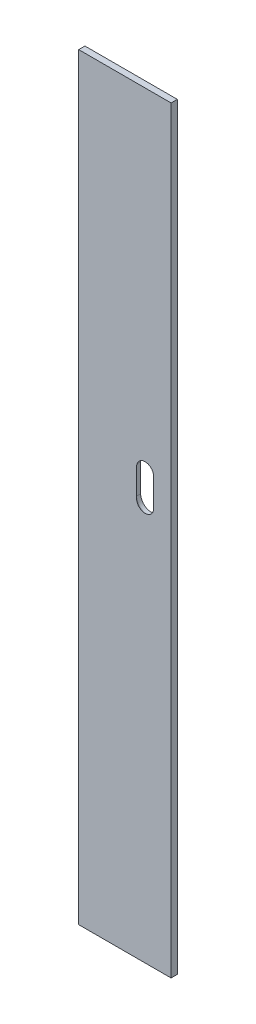
SolidWorks part; units mm, degrees
ref_plane "Front Plane" through (0, 0, 0) normal (0, 0, 1) x (1, 0, 0)
ref_plane "Top Plane" through (0, 0, 0) normal (0, 1, 0) x (1, 0, 0)
ref_plane "Right Plane" through (0, 0, 0) normal (1, 0, 0) x (0, 0, -1)
sketch "Sketch1" plane through (0, 0, 0) normal (0, 0, 1) x (1, 0, 0)
  line L1 (37, -17.9) -> (-230, -17.9)
  line L2 (37, -17.9) -> (37, 2172.1)
  line L3 (37, 2172.1) -> (-230, 2172.1)
  line L4 (-230, -17.9) -> (-230, 2172.1)
  line L6 (-230, -17.9) -> (-212, -17.9) construction
extrude "Boss-Extrude1" add sketch "Sketch1" along normal blind 18
sketch "Sketch2" plane through (0, 0, 0) normal (0, 0, -1) x (-1, 0, 0)
  line L0 (38, 1212.1) -> (38, 1132.1) construction
  line L1 (58, 1212.1) -> (58, 1132.1)
  line L2 (18, 1212.1) -> (18, 1132.1)
  line L3 (-37, 2172.1) -> (230, 2172.1) construction
  line L4 (-37, -17.9) -> (-37, 2172.1) construction
  arc A0 (58, 1212.1) -> (18, 1212.1) centre (38, 1212.1) ccw
  arc A1 (18, 1132.1) -> (58, 1132.1) centre (38, 1132.1) ccw
  point P2 (38, 1172.1)
  dimension "D1" = 1000
  dimension "D2" = 55
  dimension "E" = 40
  dimension "D3" = 80
extrude "Cut-Extrude2" cut sketch "Sketch2" against normal through all
ref_plane "Plane1" through (0, 1212.1, 0) normal (0, -1, 0) x (0, 0, -1)
sketch "Sketch5" plane through (0, 1212.1, 0) normal (0, -1, 0) x (0, 0, -1)
  line L0 (-18, -62.6) -> (0, -62.6) construction
  line L1 (0, -62.6) -> (0, -68.9)
  line L2 (-11.7, -68.9) -> (0, -68.9)
  line L4 (-18, -62.6) -> (-18, -58)
  line L5 (-18, -58) -> (0, -58)
  line L6 (0, -58) -> (0, -62.6)
  line L8 (0, -58) -> (0, -18) construction
  arc A0 (-18, -62.6) -> (-11.7, -68.9) centre (-11.7, -62.6) ccw
  dimension "D2" = 6.3
  dimension "D1" = 10.9
sketch "Sketch6" plane through (0, 0, 18) normal (0, 0, 1) x (1, 0, 0)
  line L0 (-58, 1212.1) -> (-58, 1132.1)
  line L1 (-58, 1132.1) -> (-58, 1212.1) construction
  line L2 (-18, 1132.1) -> (-18, 1212.1)
  arc A0 (-18, 1212.1) -> (-58, 1212.1) centre (-38, 1212.1) ccw construction
  arc A1 (-58, 1132.1) -> (-18, 1132.1) centre (-38, 1132.1) ccw
  arc A2 (-18, 1212.1) -> (-58, 1212.1) centre (-38, 1212.1) ccw
sweep "Cut-Sweep4" cut profiles "Sketch5" path "Sketch6"
